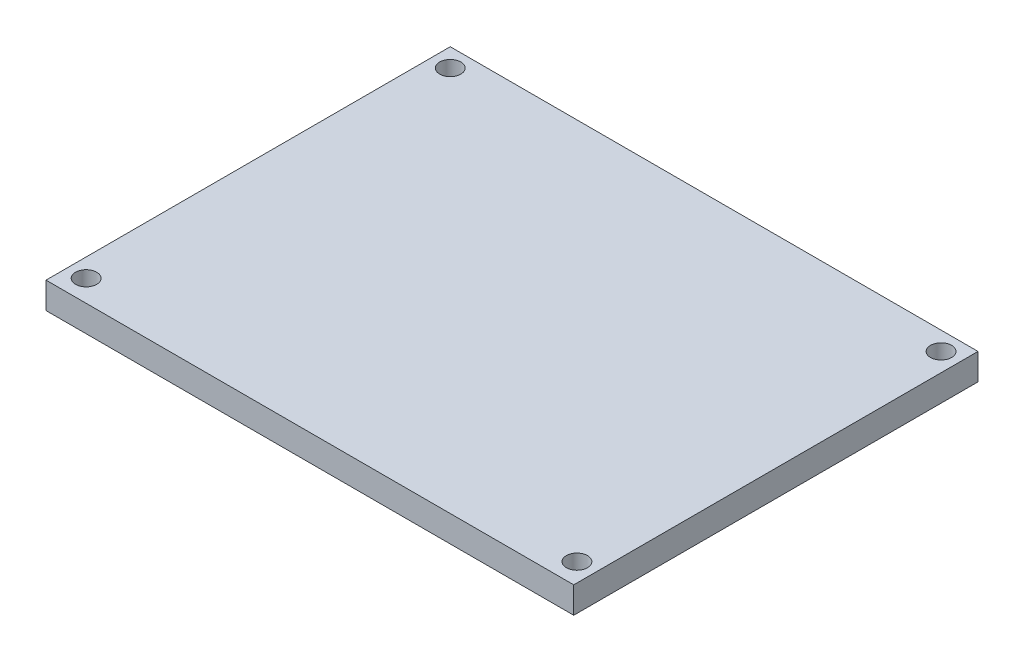
SolidWorks part; units mm, degrees
ref_plane "Front Plane" through (0, 0, 0) normal (0, 0, 1) x (1, 0, 0)
ref_plane "Top Plane" through (0, 0, 0) normal (0, 1, 0) x (1, 0, 0)
ref_plane "Right Plane" through (0, 0, 0) normal (1, 0, 0) x (0, 0, -1)
sketch "Sketch1" plane through (0, 0, 0) normal (0, 1, 0) x (1, 0, 0)
  line L1 (-50, 38.3) -> (50, 38.3)
  line L2 (-50, 38.3) -> (-50, -38.3)
  line L3 (-50, -38.3) -> (50, -38.3)
  line L4 (50, 38.3) -> (50, -38.3)
  line L5 (-50, 38.3) -> (50, -38.3) construction
  line L6 (-50, -38.3) -> (50, 38.3) construction
  point P4 (0, 0)
  dimension "D1" = 100
  dimension "D2" = 76.6
extrude "Boss-Extrude1" add sketch "Sketch1" along normal blind 5
sketch "Sketch2" plane through (0, 5, 0) normal (0, 1, 0) x (1, 0, 0)
  line L2 (0, 38.3) -> (0, -38.3) construction
  line L4 (50, 38.3) -> (-50, 38.3) construction
  line L6 (-50, -38.3) -> (50, -38.3) construction
  line L7 (-50, 0) -> (50, 0) construction
  line L8 (-50, 38.3) -> (-50, -38.3) construction
  line L9 (50, -38.3) -> (50, 38.3) construction
  circle A5 centre (-46.5, 34.8) radius 2
  circle A6 centre (46.5, 34.8) radius 2
  dimension "D1" = 4
  dimension "D2" = 3.5
  dimension "D3" = 3.5
extrude "Cut-Extrude3" cut sketch "Sketch2" against normal blind 10
sketch "Sketch3" plane through (0, 5, 0) normal (0, 1, 0) x (1, 0, 0)
  line L0 (-50, -38.3) -> (50, -38.3) construction
  line L1 (-50, 38.3) -> (-50, -38.3) construction
  line L2 (50, -38.3) -> (50, 38.3) construction
  circle A0 centre (-46.5, -34.2) radius 2
  circle A1 centre (46.5, -34.2) radius 2
  dimension "D1" = 4
  dimension "D2" = 4
  dimension "D5" = 3.5
  dimension "D3" = 4.1
  dimension "D4" = 3.5
  dimension "D6" = 4.1
extrude "Cut-Extrude4" cut sketch "Sketch3" against normal blind 10
